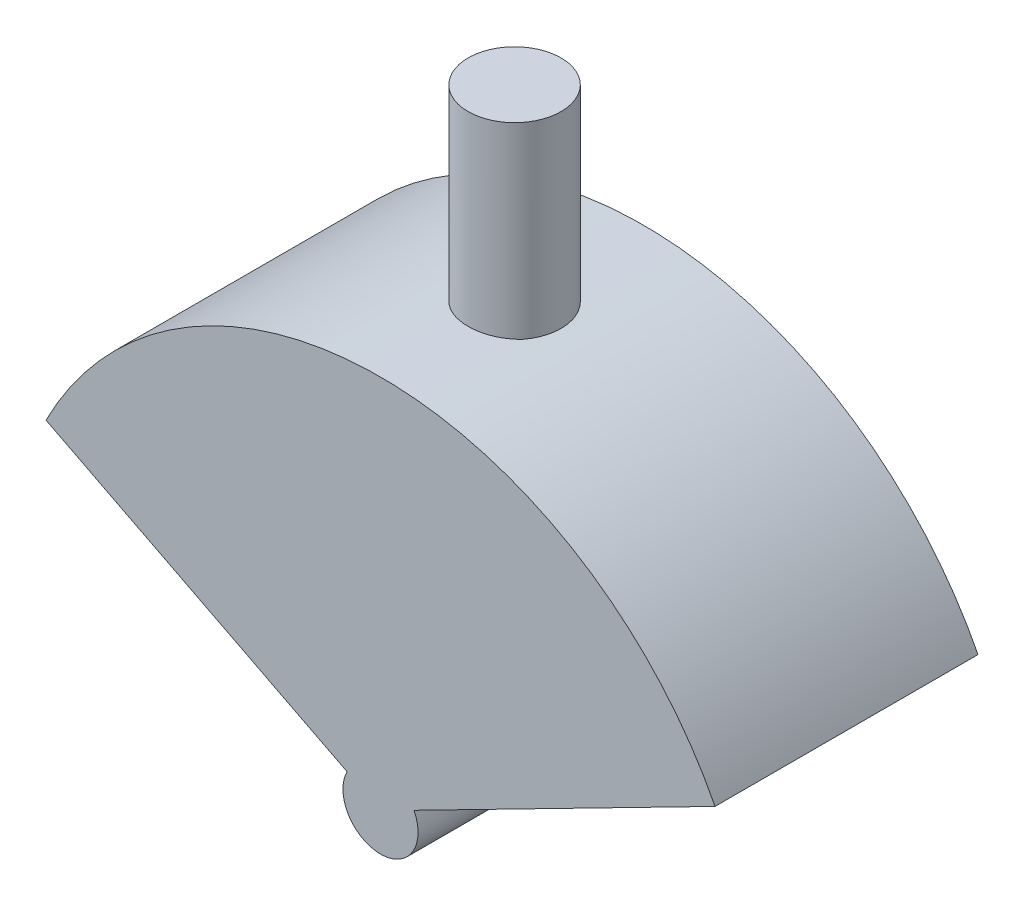
SolidWorks part; units mm, degrees
ref_plane "Front Plane" through (0, 0, 0) normal (0, 0, 1) x (1, 0, 0)
ref_plane "Top Plane" through (0, 0, 0) normal (0, 1, 0) x (1, 0, 0)
ref_plane "Right Plane" through (0, 0, 0) normal (1, 0, 0) x (0, 0, -1)
sketch "Sketch2" plane through (0, 0, 0) normal (0, 0, 1) x (1, 0, 0)
  line L0 (0, 0) -> (-44.5204, 22.7583)
  line L1 (0, 0) -> (0, 50) construction
  line L2 (0, 0) -> (44.5204, 22.7583)
  arc A0 (44.5204, 22.7583) -> (-44.5204, 22.7583) centre (0, 0) ccw
  dimension "D1" = 100
extrude "Boss-Extrude1" add sketch "Sketch2" along normal blind 35
shell "Shell1" thickness 2
sketch "Sketch3" plane through (0, 0, 35) normal (0, 0, 1) x (1, 0, 0)
  circle A0 centre (0, 0) radius 5
  dimension "D1" = 10
extrude "Boss-Extrude2" add sketch "Sketch3" against normal blind 35
ref_plane "Plane1" through (0, 49.7581, 0) normal (0, 1, 0) x (1, 0, 0)
sketch "Sketch4" plane through (0, 49.7581, 0) normal (0, 1, 0) x (1, 0, 0)
  circle A0 centre (0, -17.1572) radius 6.1885
  point P2 (0, -17.1572)
extrude "Boss-Extrude3" add sketch "Sketch4" along normal blind 25
